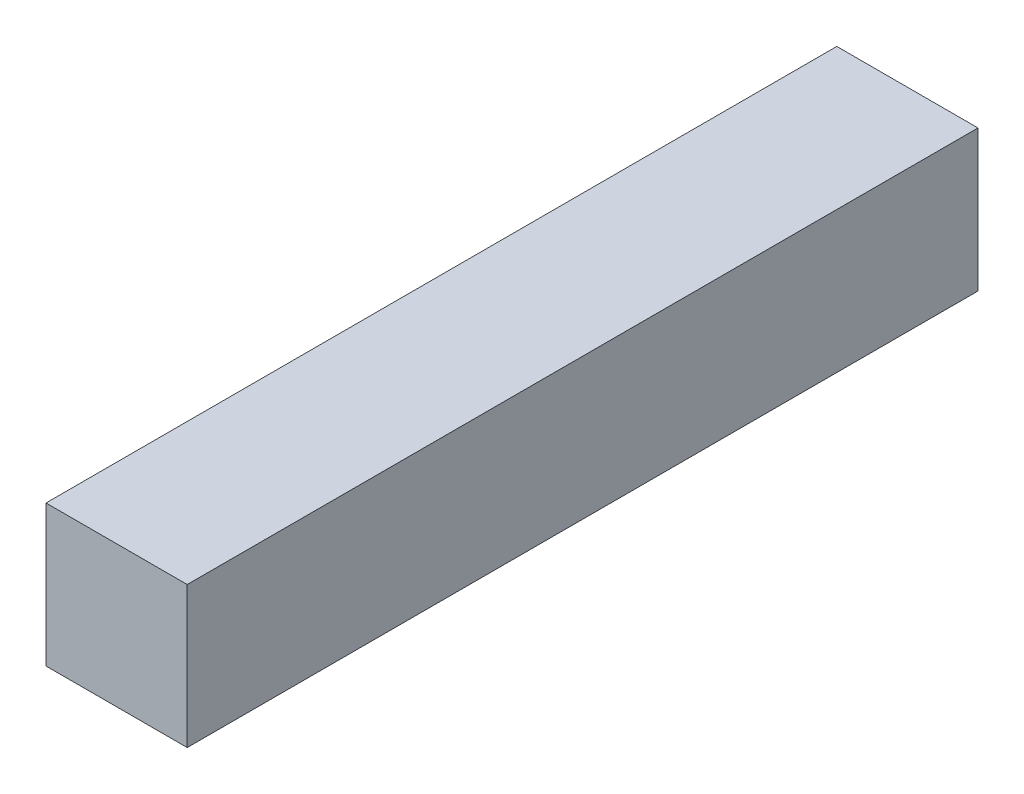
SolidWorks part; units mm, degrees
ref_plane "Front Plane" through (0, 0, 0) normal (0, 0, 1) x (1, 0, 0)
ref_plane "Top Plane" through (0, 0, 0) normal (0, 1, 0) x (1, 0, 0)
ref_plane "Right Plane" through (0, 0, 0) normal (1, 0, 0) x (0, 0, -1)
sketch "Sketch1" plane through (0, 0, 0) normal (0, 0, 1) x (1, 0, 0)
  line L1 (0, 0) -> (3.175, 0)
  line L2 (0, 0) -> (0, 3.175)
  line L3 (0, 3.175) -> (3.175, 3.175)
  line L4 (3.175, 0) -> (3.175, 3.175)
  dimension "D1" = 3.175
  dimension "D2" = 3.175
extrude "Boss-Extrude1" add sketch "Sketch1" along normal blind 17.78
